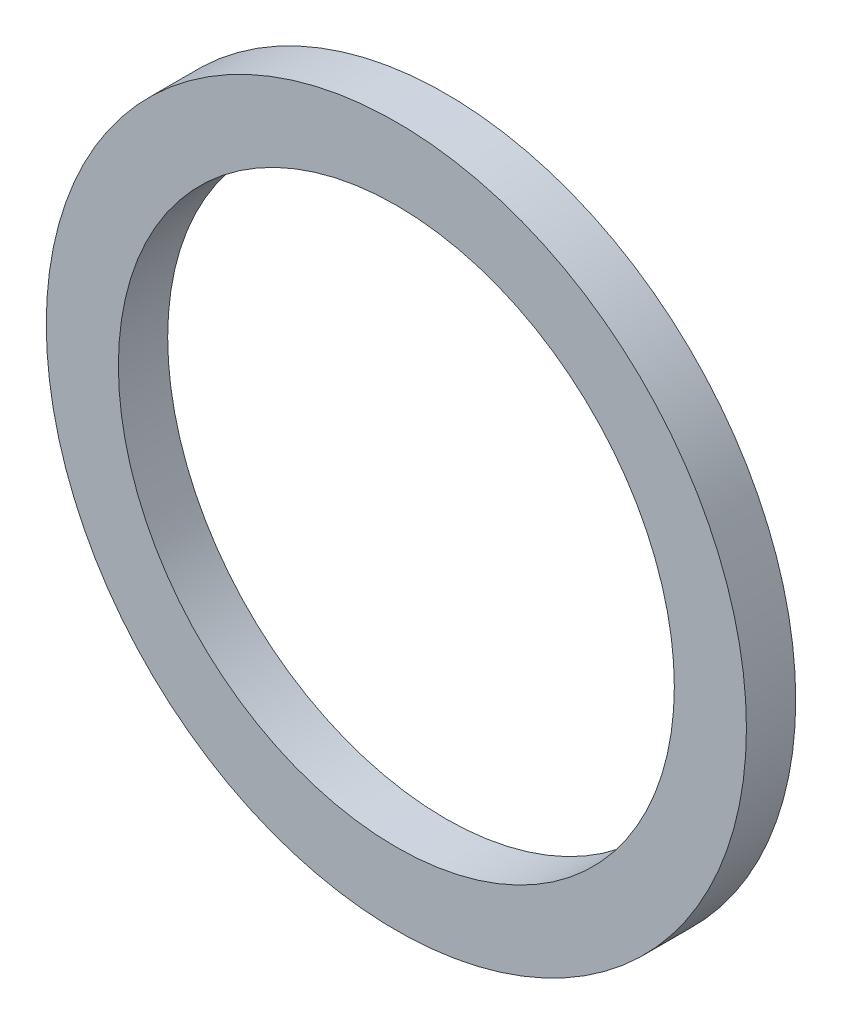
SolidWorks part; units mm, degrees
material "Plain Carbon Steel"
ref_plane "Front Plane" through (0, 0, 0) normal (0, 0, 1) x (1, 0, 0)
ref_plane "Top Plane" through (0, 0, 0) normal (0, 1, 0) x (1, 0, 0)
ref_plane "Right Plane" through (0, 0, 0) normal (1, 0, 0) x (0, 0, -1)
sketch "Sketch1" plane through (0, 0, 0) normal (0, 0, 1) x (1, 0, 0)
  circle A0 centre (0, 0) radius 22.5425
  circle A1 centre (0, 0) radius 17.9
  dimension "D1" = 45.085
  dimension "D2" = 35.8
extrude "Boss-Extrude1" add sketch "Sketch1" along normal blind 3.175
